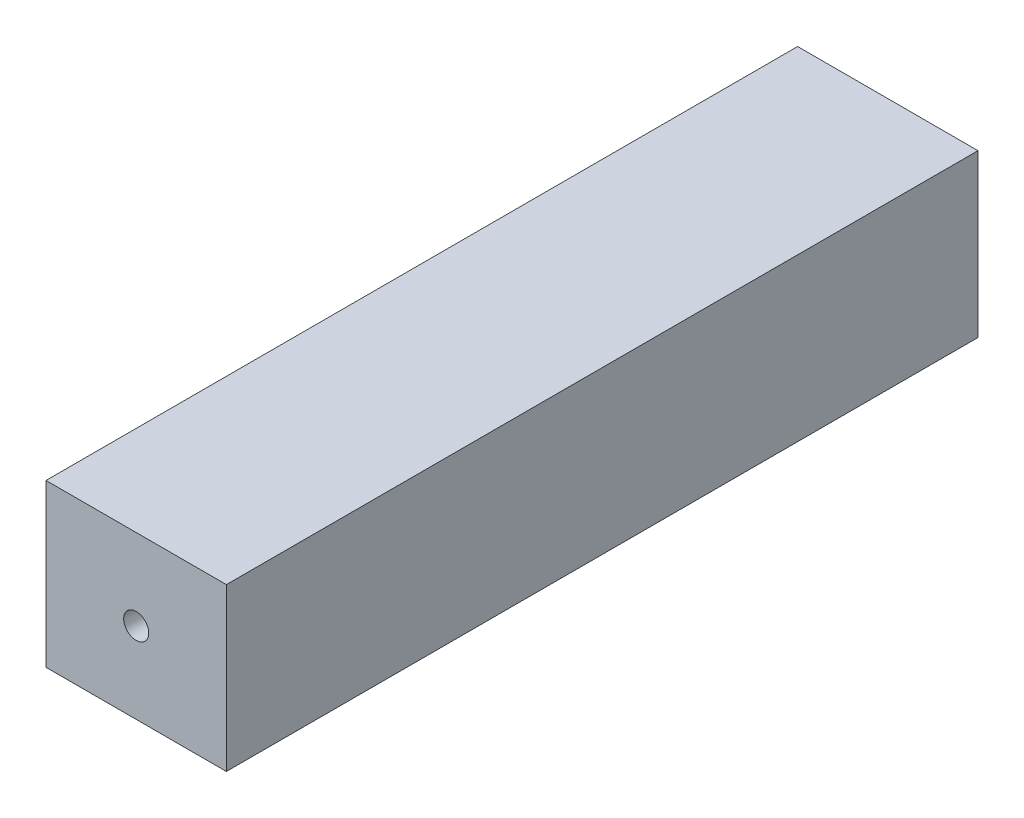
SolidWorks part; units mm, degrees
ref_plane "前视基准面" through (0, 0, 0) normal (0, 0, 1) x (1, 0, 0)
ref_plane "上视基准面" through (0, 0, 0) normal (0, 1, 0) x (1, 0, 0)
ref_plane "右视基准面" through (0, 0, 0) normal (1, 0, 0) x (0, 0, -1)
sketch "草图2" plane through (0, 0, 0) normal (0, 0, 1) x (1, 0, 0)
  line L1 (-111.4109, 2.5187) -> (-75.4109, 2.5187)
  line L2 (-111.4109, 2.5187) -> (-111.4109, 34.8187)
  line L3 (-111.4109, 34.8187) -> (-75.4109, 34.8187)
  line L4 (-75.4109, 2.5187) -> (-75.4109, 34.8187)
  dimension "D1" = 36
  dimension "D2" = 32.3
extrude "凸台-拉伸1" add sketch "草图2" along normal blind 150
sketch "草图4" plane through (0, 0, 150) normal (0, 0, 1) x (1, 0, 0)
  line L0 (-75.4109, 2.5187) -> (-111.4109, 34.8187) construction
  line L1 (-75.4109, 34.8187) -> (-111.4109, 2.5187) construction
hole_wizard "M6 螺纹孔1" positions "草图7" profile "草图8" tap size "M6" standard "GB"
sketch "草图7" plane through (0, 0, 150) normal (0, 0, 1) x (1, 0, 0)
  line L0 (-75.4109, 2.5187) -> (-111.4109, 34.8187) construction
  point P0 (-93.4109, 18.6687)
sketch "草图8" plane through (-93.4109, 18.6687, 150) normal (1, 0, 0) x (0, -1, 0)
  line L0 (0, 0) -> (0, 8.5022)
  line L1 (0, 8.5022) -> (2.5, 7)
  line L2 (2.5, 7) -> (2.5, 0)
  line L5 (2.5, 0) -> (0, 0)
  line L10 (0, 8.5022) -> (-2.5, 7) construction
  line L11 (0, -6.35) -> (0, 107.95) construction
  dimension "螺纹孔钻头直径" = 5
  dimension "螺纹孔钻头深度" = 7
  dimension "导头角度" = 118
cosmetic thread "孔螺蚊线1" parameters "D1"=6, "D2"=6
